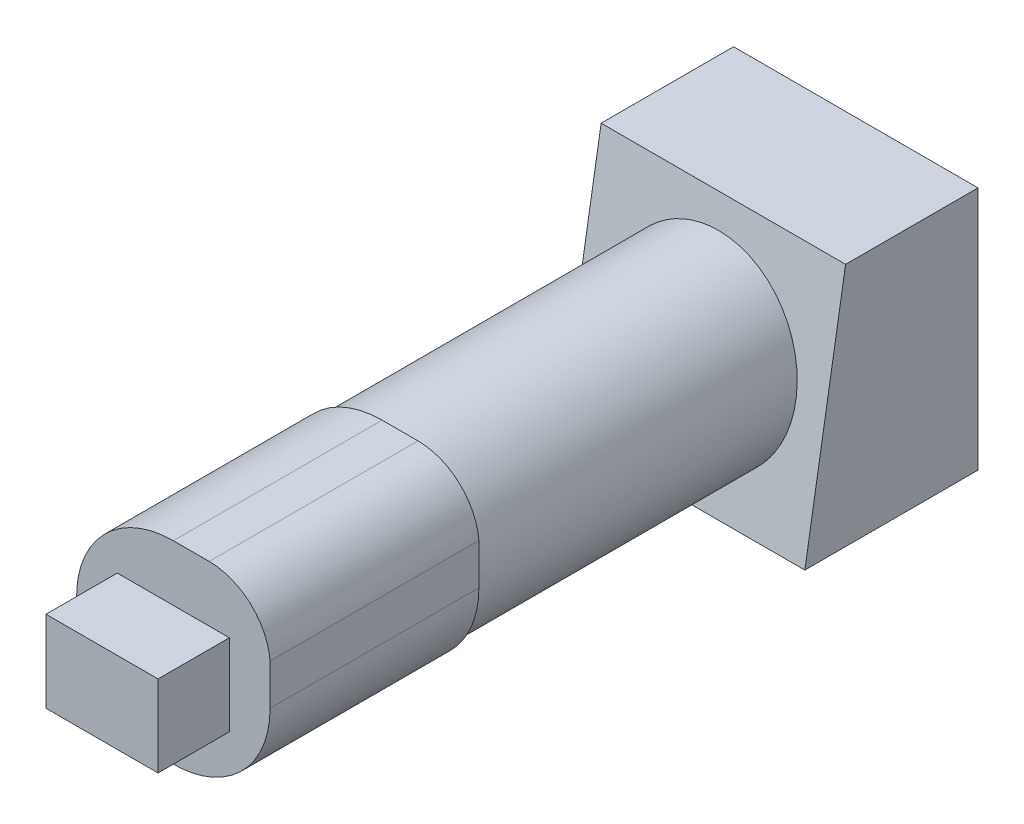
SolidWorks part; units mm, degrees
ref_plane "Alzado" through (0, 0, 0) normal (0, 0, 1) x (1, 0, 0)
ref_plane "Planta" through (0, 0, 0) normal (0, 1, 0) x (1, 0, 0)
ref_plane "Vista lateral" through (0, 0, 0) normal (1, 0, 0) x (0, 0, -1)
sketch "Croquis1" plane through (0, 0, 0) normal (0, 1, 0) x (1, 0, 0)
  line L1 (-12, -8.5) -> (12, -8.5)
  line L2 (-12, -8.5) -> (-12, 8.5)
  line L3 (-12, 8.5) -> (12, 8.5)
  line L4 (12, -8.5) -> (12, 8.5)
  line L5 (-12, -8.5) -> (12, 8.5) construction
  line L6 (-12, 8.5) -> (12, -8.5) construction
  point P0 (0, 0)
  dimension "D1" = 24
  dimension "D2" = 17
extrude "Saliente-Extruir1" add sketch "Croquis1" along normal blind 24
sketch "Croquis2" plane through (12, 0, 0) normal (1, 0, 0) x (0, 0, -1)
  line L0 (-8.5, 0) -> (-4.5001, 24)
  line L1 (-8.5, 24) -> (8.5, 24) construction
  line L2 (-8.5, 0) -> (8.5, 0) construction
  line L3 (-4.5001, 24) -> (-8.5, 24)
  line L4 (-8.5, 24) -> (-8.5, 0)
  dimension "D1" = 80.538
extrude "Cortar-Extruir1" cut sketch "Croquis2" against normal blind 24
ref_plane "Plano1" through (0, 0, 4.5001) normal (0, 0, -1) x (1, 0, 0)
sketch "Croquis4" plane through (0, 0, 4.5001) normal (0, 0, -1) x (1, 0, 0)
  line L0 (0, -24) -> (0, 0) construction
  line L1 (-12, -24) -> (12, -24) construction
  circle A0 centre (0, -12) radius 9.125
  dimension "D1" = 18.25
extrude "Saliente-Extruir3" add sketch "Croquis4" against normal blind 33.5
sketch "Croquis5" plane through (0, 0, 38.0001) normal (0, 0, 1) x (1, 0, 0)
  line L0 (0, 21.5) -> (3.5228, 21.5)
  line L1 (9.5, 12) -> (9.5, 16.023)
  arc A0 (0, 21.5) -> (9.5, 12) centre (0, 12) ccw
  arc A1 (3.5228, 21.5) -> (9.5, 16.023) centre (3.5228, 15.5) cw
  dimension "D1" = 19
  dimension "D2" = 6
extrude "Saliente-Extruir4" add sketch "Croquis5" along normal blind 20.5
sketch "Croquis6" plane through (0, 0, 58.5001) normal (0, 0, 1) x (1, 0, 0)
  line L1 (-5.5, 8) -> (5.5, 8)
  line L2 (-5.5, 8) -> (-5.5, 16)
  line L3 (-5.5, 16) -> (5.5, 16)
  line L4 (5.5, 8) -> (5.5, 16)
  line L5 (-5.5, 8) -> (5.5, 16) construction
  line L6 (-5.5, 16) -> (5.5, 8) construction
  point P0 (0, 12)
  dimension "D1" = 11
  dimension "D2" = 8
extrude "Saliente-Extruir5" add sketch "Croquis6" along normal blind 7
sketch "Croquis7" plane through (0, 0, 0) normal (0, -1, 0) x (1, 0, 0)
  line L0 (-12, -8.5) -> (-12, 8.5) construction
  line L1 (12, 8.5) -> (12, -8.5) construction
  line L2 (-12, 8.5) -> (12, 8.5) construction
  circle A0 centre (-5, 3.5) radius 2.05
  circle A1 centre (5, 3.5) radius 2.05
  dimension "D1" = 4.1
  dimension "D2" = 4.1
  dimension "D3" = 5
  dimension "D4" = 7
  dimension "D5" = 7
  dimension "D6" = 5
extrude "Cortar-Extruir2" cut sketch "Croquis7" against normal blind 6
